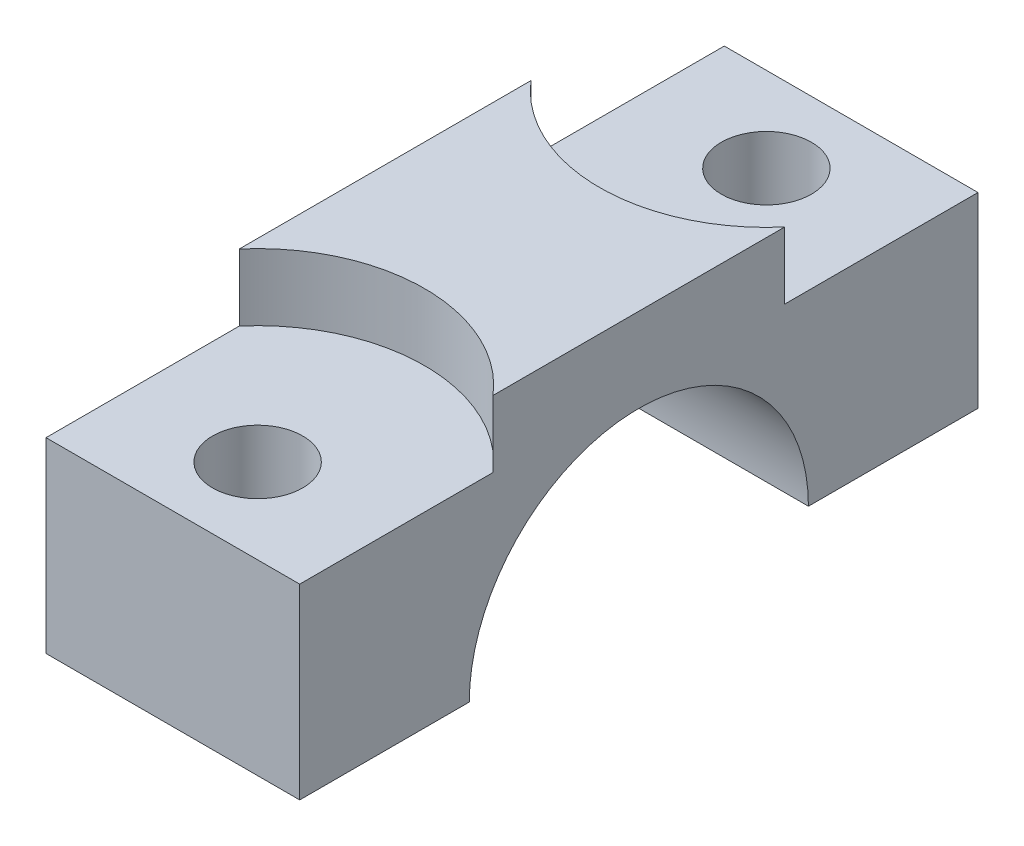
SolidWorks part; units mm, degrees
ref_plane "Front Plane" through (0, 0, 0) normal (0, 0, 1) x (1, 0, 0)
ref_plane "Top Plane" through (0, 0, 0) normal (0, 1, 0) x (1, 0, 0)
ref_plane "Right Plane" through (0, 0, 0) normal (1, 0, 0) x (0, 0, -1)
sketch "Sketch1" plane through (0, 0, 0) normal (1, 0, 0) x (0, 0, -1)
  line L0 (12.7, 0) -> (25.4, 0)
  line L1 (-25.4, 19) -> (25.4, 19)
  line L2 (-25.4, 19) -> (-25.4, 0)
  line L3 (-25.4, 0) -> (-12.7, 0)
  line L4 (25.4, 19) -> (25.4, 0)
  arc A0 (-12.7, 0) -> (12.7, 0) centre (0, 0) cw
  dimension "D3" = 12.7
  dimension "D1" = 50.8
  dimension "D2" = 19
extrude "Boss-Extrude1" add sketch "Sketch1" along normal mid plane 19
sketch "Sketch2" plane through (0, 0, 0) normal (0, -1, 0) x (1, 0, 0)
  line L0 (-9.5, 19.05) -> (9.5, 19.05) construction
  line L1 (-9.5, 25.4) -> (-9.5, 12.7) construction
  line L2 (9.5, 25.4) -> (9.5, 12.7) construction
  line L3 (-9.5, -19.05) -> (9.5, -19.05) construction
  line L5 (9.5, -12.7) -> (9.5, -25.4) construction
  line L6 (-9.5, -12.7) -> (-9.5, -25.4) construction
  point P9 (0, -19.05)
hole_wizard "CBORE for M12 Hex Head Cap Screw2" positions "3DSketch2" profile "Sketch5" counterbore size "M12" standard "ISO" end condition through all
sketch3d "3DSketch2"
  line L0 (-9.5, 0, 19.05) -> (9.5, 0, 19.05) construction
  point P0 (0, 19, 19.05)
  point P2 (0, 19, -19.05)
  point P10 (0, 0, 19.05)
sketch "Sketch5" plane through (0, 19, 19.05) normal (1, 0, 0) x (0, 0, 1)
  line L0 (0, 0) -> (0, 19)
  line L1 (0, 19) -> (3.375, 19)
  line L3 (3.375, 19) -> (3.375, 5)
  line L4 (3.375, 5) -> (12.5, 5)
  line L5 (12.5, 5) -> (12.5, 0)
  line L7 (12.5, 0) -> (0, 0)
  line L11 (0, -6.35) -> (0, 107.95) construction
  dimension "Thru Hole Dia." = 6.75
  dimension "Thru Hole Depth" = 19
  dimension "C'Bore Dia." = 25
  dimension "C'Bore Depth" = 5
